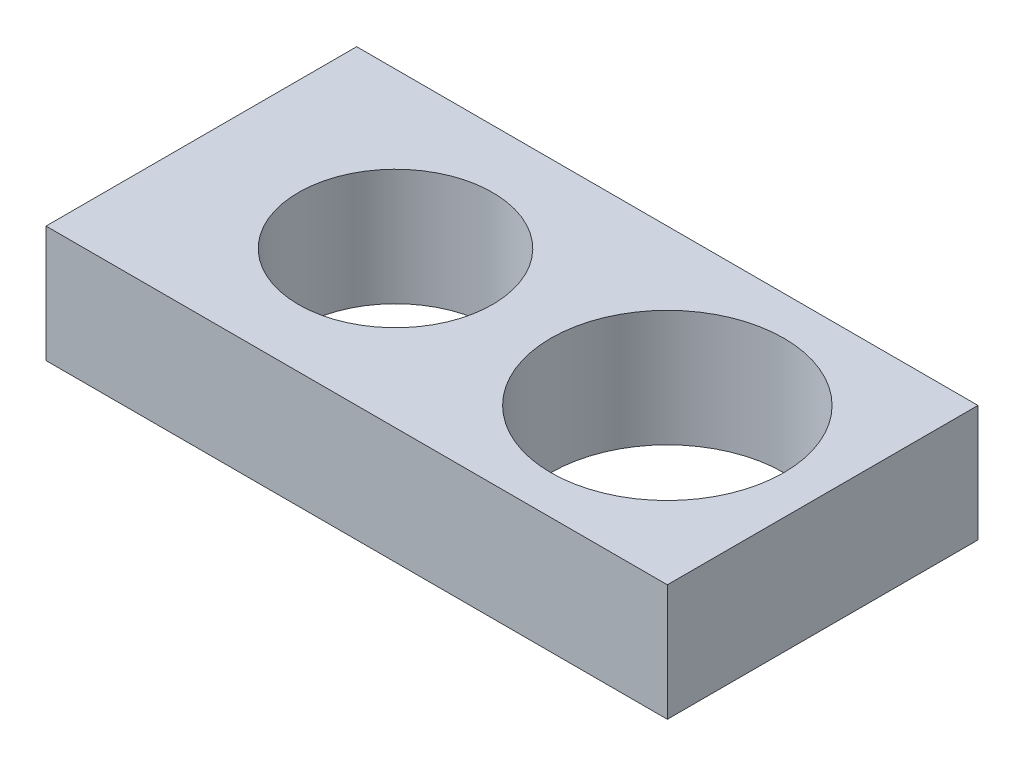
SolidWorks part; units mm, degrees
ref_plane "Front Plane" through (0, 0, 0) normal (0, 0, 1) x (1, 0, 0)
ref_plane "Top Plane" through (0, 0, 0) normal (0, 1, 0) x (1, 0, 0)
ref_plane "Right Plane" through (0, 0, 0) normal (1, 0, 0) x (0, 0, -1)
sketch "Sketch2" plane through (0, 0, 0) normal (0, 1, 0) x (1, 0, 0)
  line L1 (-40, -20) -> (40, -20)
  line L2 (-40, -20) -> (-40, 20)
  line L3 (-40, 20) -> (40, 20)
  line L4 (40, -20) -> (40, 20)
  line L5 (-40, -20) -> (40, 20) construction
  line L6 (-40, 20) -> (40, -20) construction
  circle A0 centre (-15, 0) radius 12.5
  circle A1 centre (20, 0) radius 15
  point P0 (0, 0)
  dimension "D3" = 25
  dimension "D4" = 30
  dimension "D1" = 40
  dimension "D2" = 80
  dimension "D5" = 15
  dimension "D6" = 20
extrude "Boss-Extrude1" add sketch "Sketch2" along normal blind 15
